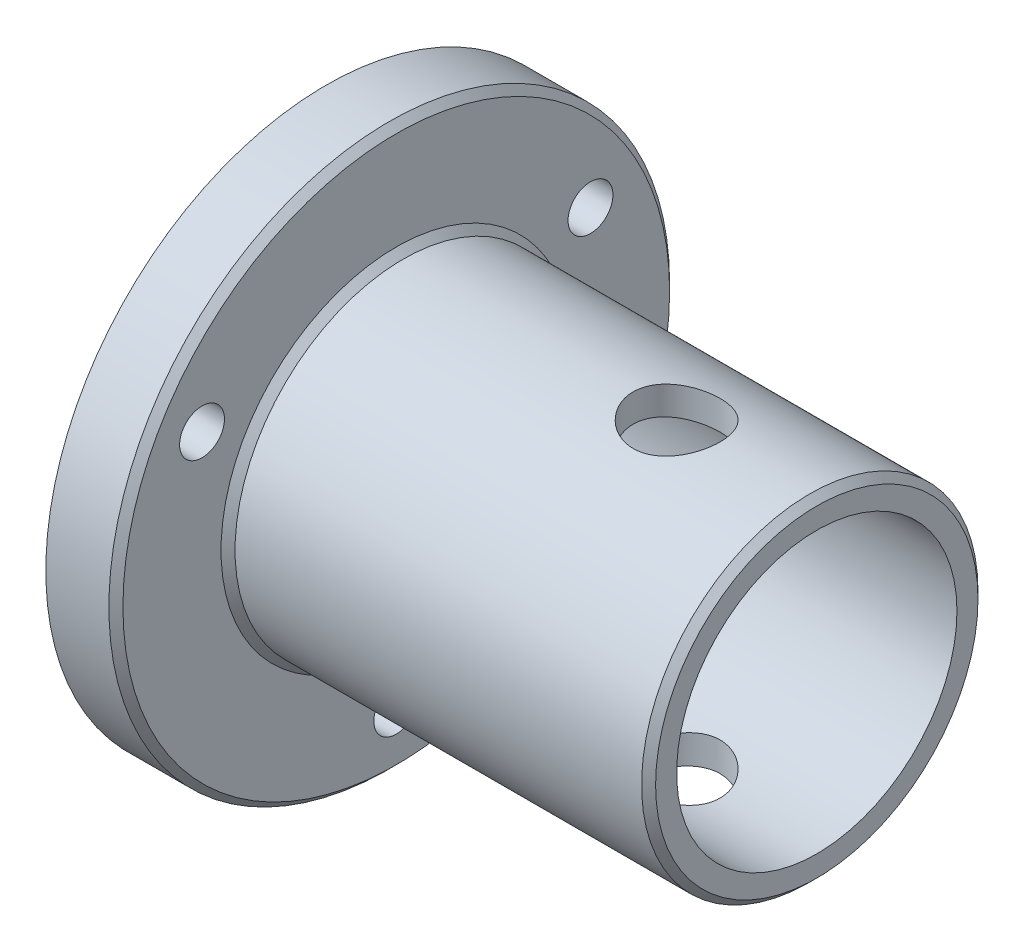
SolidWorks part; units mm, degrees
ref_plane "Front" through (0, 0, 0) normal (0, 0, 1) x (1, 0, 0)
ref_plane "Top" through (0, 0, 0) normal (0, 1, 0) x (1, 0, 0)
ref_plane "Right" through (0, 0, 0) normal (1, 0, 0) x (0, 0, -1)
sketch "草图1" plane through (0, 0, 0) normal (1, 0, 0) x (0, 0, -1)
  line L0 (0, 0) -> (0, -16) construction
  line L1 (0, 0) -> (13.8564, 8) construction
  line L2 (0, 0) -> (-13.8564, 8) construction
  circle A0 centre (0, 0) radius 10
  circle A1 centre (0, 0) radius 20
  circle A2 centre (0, 0) radius 16 construction
  circle A3 centre (0, 0) radius 12
  circle A4 centre (-13.8564, 8) radius 1.6
  circle A5 centre (13.8564, 8) radius 1.6
  circle A6 centre (0, -16) radius 1.6
extrude "凸台-拉伸1" add sketch "草图1" along normal blind 5 contours A1
sketch "草图6" plane through (5, 0, 0) normal (1, 0, 0) x (0, 0, -1)
  circle A0 centre (0, 0) radius 10
  circle A1 centre (0, 0) radius 12
extrude "凸台-拉伸2" add sketch "草图6" along normal blind 30 contours A1
sketch "草图7" plane through (35, 0, 0) normal (1, 0, 0) x (0, 0, -1)
  circle A0 centre (0, 0) radius 10
extrude "切除-拉伸2" cut sketch "草图7" against normal blind 30
chamfer "倒角1" distance 0.5 angle 45 1 edges at (35, 0, -12)
sketch "草图8" plane through (0, 0, 0) normal (0, 1, 0) x (1, 0, 0)
  line L0 (5, 0) -> (25, 0) construction
  line L1 (5, -20) -> (5, 20) construction
  circle A0 centre (25, 0) radius 3.1
extrude "切除-拉伸3" cut sketch "草图8" along normal through all both and the other way through all
chamfer "倒角2" distance 0.5 angle 45 1 edges at (5, 0, -20)
chamfer "倒角3" distance 0.5 angle 45 1 edges at (5, 0, -12)
sketch "草图9" plane through (0, 0, 0) normal (-1, 0, 0) x (0, 0, 1)
  circle A0 centre (-13.8564, 8) radius 1.6
  circle A1 centre (13.8564, 8) radius 1.6
  circle A2 centre (0, -16) radius 1.6
extrude "切除-拉伸4" cut sketch "草图9" against normal blind 10
